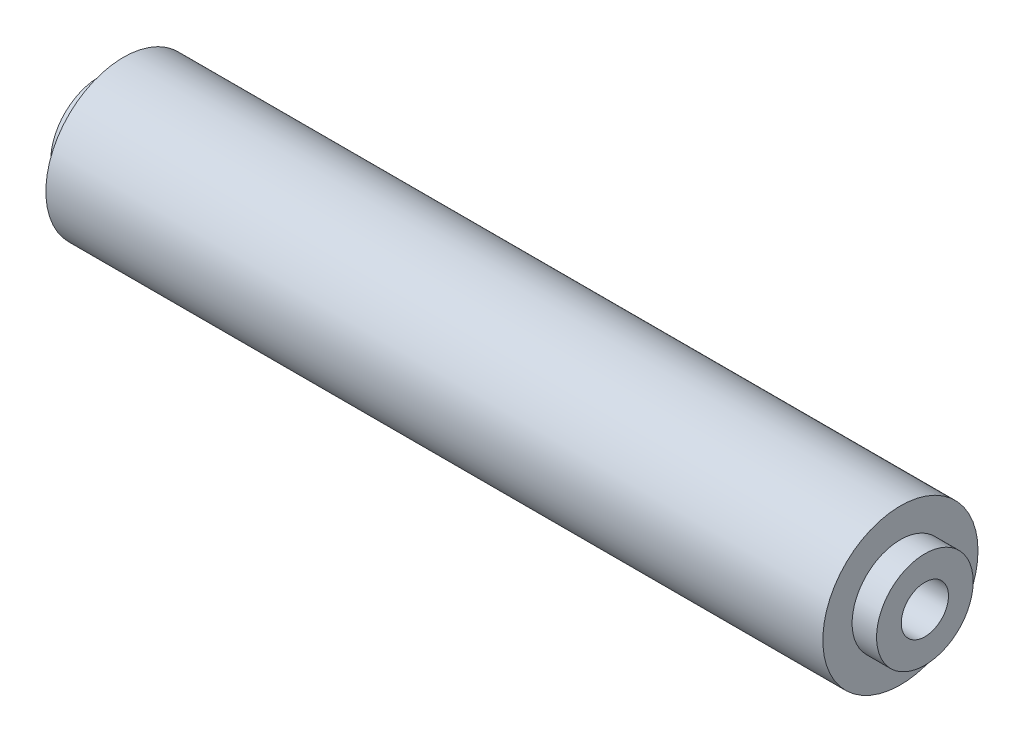
SolidWorks part; units mm, degrees
ref_plane "Front Plane" through (0, 0, 0) normal (0, 0, 1) x (1, 0, 0)
ref_plane "Top Plane" through (0, 0, 0) normal (0, 1, 0) x (1, 0, 0)
ref_plane "Right Plane" through (0, 0, 0) normal (1, 0, 0) x (0, 0, -1)
sketch "Sketch4" plane through (0, 0, 0) normal (1, 0, 0) x (0, 0, -1)
  circle A0 centre (0, 0) radius 4.5847
  circle A1 centre (0, 0) radius 9.3853
  dimension "D1" = 9.1694
  dimension "D2" = 18.7706
extrude "Boss-Extrude1" add sketch "Sketch4" along normal blind 4.7498
sketch "Sketch5" plane through (4.7498, 0, 0) normal (1, 0, 0) x (0, 0, -1)
  circle A0 centre (0, 0) radius 15.0762
  dimension "D1" = 30.1523
extrude "Boss-Extrude2" add sketch "Sketch5" along normal blind 75.4831
ref_plane "Plane1" through (80.2329, 0, 0) normal (1, 0, 0) x (0, 0, -1)
mirror "Mirror3" about plane through (80.2329, 0, 0) normal (1, 0, 0) of "Boss-Extrude2"
mirror "Mirror4" about plane through (80.2329, 0, 0) normal (1, 0, 0) of "Boss-Extrude1"
sketch "Sketch6" plane through (155.7161, 0, 0) normal (1, 0, 0) x (0, 0, -1)
  circle A0 centre (0, 0) radius 4.5847
extrude "Cut-Extrude1" cut sketch "Sketch6" against normal through all
